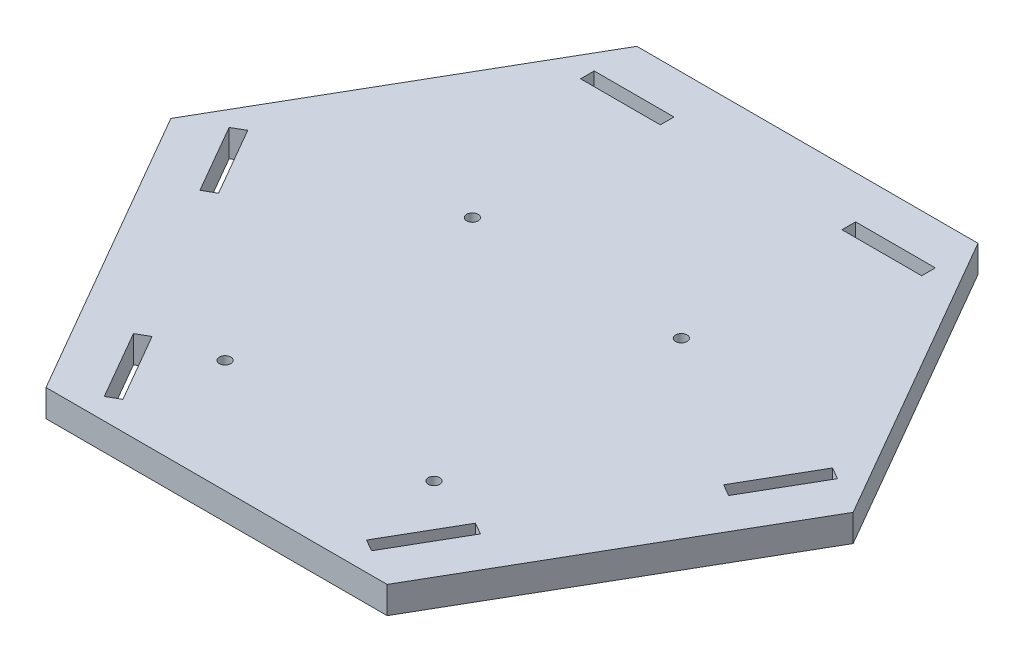
SolidWorks part; units mm, degrees
ref_plane "Front Plane" through (0, 0, 0) normal (0, 0, 1) x (1, 0, 0)
ref_plane "Top Plane" through (0, 0, 0) normal (0, 1, 0) x (1, 0, 0)
ref_plane "Right Plane" through (0, 0, 0) normal (1, 0, 0) x (0, 0, -1)
sketch "Sketch1" plane through (0, 0, 0) normal (0, 1, 0) x (1, 0, 0)
  line L0 (40, -69.282) -> (80, 0)
  line L1 (80, 0) -> (40, 69.282)
  line L2 (-40, 69.282) -> (-80, 0)
  line L3 (-40, -69.282) -> (40, -69.282)
  line L4 (-80, 0) -> (-40, -69.282)
  line L5 (-40, 69.282) -> (40, 69.282)
  line L6 (0, 69.282) -> (0, -69.282) construction
  line L7 (60, -34.641) -> (-60, 34.641) construction
  line L8 (-80, 0) -> (-58.4498, 12.442) construction
  line L9 (-60, -34.641) -> (0, 0) construction
  line L10 (-70.65, -16.1947) -> (-49.0998, -3.7526) construction
  line L11 (-68.5685, 6.6) -> (-59.2185, -9.5947)
  line L12 (-59.2185, -9.5947) -> (-61.9897, -11.1947)
  line L13 (-61.9897, -11.1947) -> (-71.3397, 5)
  line L14 (-71.3397, 5) -> (-68.5685, 6.6)
  line L16 (-31.3397, -64.282) -> (-28.5685, -62.682)
  line L17 (-40.6897, -48.0874) -> (-31.3397, -64.282)
  line L18 (-37.9185, -46.4874) -> (-40.6897, -48.0874)
  line L19 (-28.5685, -62.682) -> (-37.9185, -46.4874)
  line L20 (28.5685, -62.682) -> (37.9185, -46.4874)
  line L21 (37.9185, -46.4874) -> (40.6897, -48.0874)
  line L22 (40.6897, -48.0874) -> (31.3397, -64.282)
  line L23 (31.3397, -64.282) -> (28.5685, -62.682)
  line L24 (71.3397, 5) -> (68.5685, 6.6)
  line L25 (61.9897, -11.1947) -> (71.3397, 5)
  line L26 (59.2185, -9.5947) -> (61.9897, -11.1947)
  line L27 (68.5685, 6.6) -> (59.2185, -9.5947)
  line L28 (40, 56.082) -> (21.3, 56.082)
  line L29 (21.3, 56.082) -> (21.3, 59.282)
  line L30 (21.3, 59.282) -> (40, 59.282)
  line L31 (40, 59.282) -> (40, 56.082)
  line L32 (-40, 59.282) -> (-40, 56.082)
  line L33 (-21.3, 59.282) -> (-40, 59.282)
  line L34 (-21.3, 56.082) -> (-21.3, 59.282)
  line L35 (-40, 56.082) -> (-21.3, 56.082)
  circle A0 centre (0, 0) radius 69.282 construction
  point P13 (-75.325, -8.0973)
  point P35 (75.325, -8.0973)
  dimension "D1" = 80
  dimension "D2" = 80
  dimension "D3" = 9.35
  dimension "D4" = 18.7
  dimension "D5" = 9.35
  dimension "D6" = 3.2
  dimension "D7" = 10
extrude "Boss-Extrude1" add sketch "Sketch1" along normal blind 6.35
sketch "Sketch2" plane through (0, 6.35, 0) normal (0, 1, 0) x (1, 0, 0)
  line L1 (-24.5, -42.782) -> (24.5, -42.782) construction
  line L2 (-24.5, -42.782) -> (-24.5, 15.218) construction
  line L3 (-24.5, 15.218) -> (24.5, 15.218) construction
  line L4 (24.5, -42.782) -> (24.5, 15.218) construction
  line L5 (-24.5, -42.782) -> (24.5, 15.218) construction
  line L6 (-24.5, 15.218) -> (24.5, -42.782) construction
  line L7 (-40, -69.282) -> (40, -69.282) construction
  circle A0 centre (-24.5, -42.782) radius 1.35
  circle A1 centre (24.5, -42.782) radius 1.35
  circle A2 centre (24.5, 15.218) radius 1.35
  circle A3 centre (-24.5, 15.218) radius 1.35
  point P0 (0, -13.782)
  point P9 (0, 15.218)
  dimension "D2" = 2.7
  dimension "D1" = 58
  dimension "D3" = 49
  dimension "D4" = 26.5
  dimension "D5" = 0
extrude "Cut-Extrude1" cut sketch "Sketch2" against normal up to surface (6.35 mm away) up to face at (30.65, 0, -57.682)
equation "\"D5@Sketch1\"=\"D4@Sketch1\"/2"
equation "\"D3@Sketch1\"=\"D5@Sketch1\""
